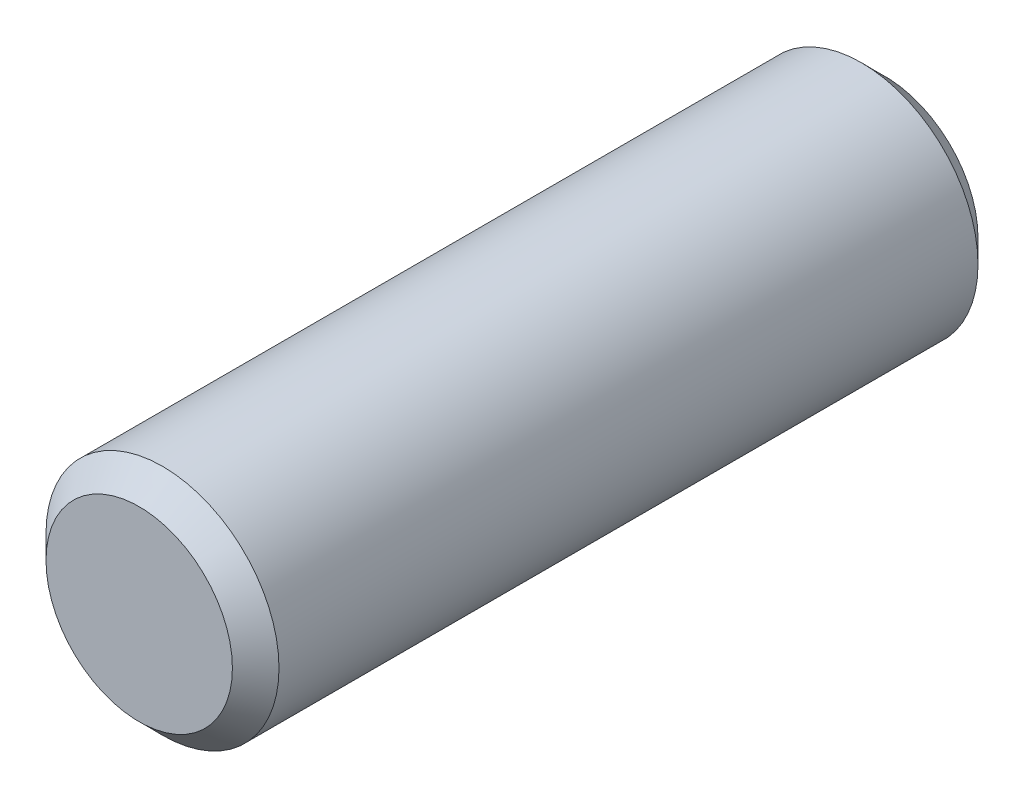
SolidWorks part; units mm, degrees
ref_plane "Front Plane" through (0, 0, 0) normal (0, 0, 1) x (1, 0, 0)
ref_plane "Top Plane" through (0, 0, 0) normal (0, 1, 0) x (1, 0, 0)
ref_plane "Right Plane" through (0, 0, 0) normal (1, 0, 0) x (0, 0, -1)
sketch "Sketch2" plane through (0, 0, 0) normal (0, 0, 1) x (1, 0, 0)
  circle A0 centre (0, 0) radius 5
  dimension "D1" = 10
extrude "Boss-Extrude1" add sketch "Sketch2" along normal blind 32
chamfer "Chamfer1" distance 1 angle 45 2 edges at (5, 0, 0) (5, 0, 32)
